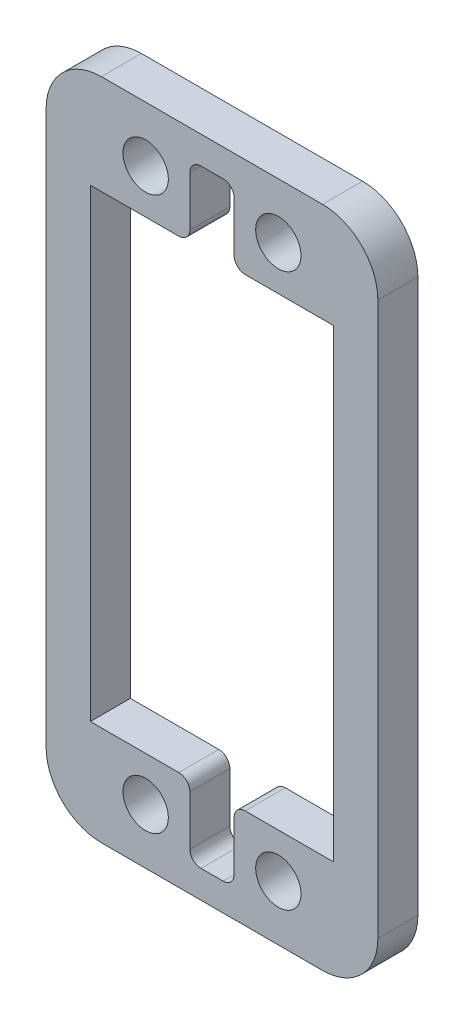
SolidWorks part; units mm, degrees
ref_plane "Alzado" through (0, 0, 0) normal (0, 0, 1) x (1, 0, 0)
ref_plane "Planta" through (0, 0, 0) normal (0, 1, 0) x (1, 0, 0)
ref_plane "Vista lateral" through (0, 0, 0) normal (1, 0, 0) x (0, 0, -1)
sketch "Croquis1" plane through (0, 0, 0) normal (0, 0, 1) x (1, 0, 0)
  line L0 (-15, 30) -> (15, 30)
  line L1 (15, 30) -> (15, -30)
  line L2 (15, -30) -> (-15, -30)
  line L3 (-15, -30) -> (-15, 30)
  line L4 (0, 0) -> (3.1755, 0) construction
  line L5 (0, 0) -> (0, 1.2752) construction
  dimension "D1" = 60
  dimension "D2" = 30
extrude "Saliente-Extruir1" add sketch "Croquis1" along normal blind 3.62
sketch "Croquis2" plane through (0, 0, 0) normal (0, 0, -1) x (-1, 0, 0)
  line L0 (-11, 21) -> (11, 21)
  line L1 (11, 21) -> (11, -21)
  line L2 (11, -21) -> (-11, -21)
  line L3 (-11, -21) -> (-11, 21)
  line L4 (0, 0) -> (17.9824, 0) construction
  line L5 (0, 0) -> (0, 11.2002) construction
  dimension "D1" = 22
  dimension "D2" = 42
extrude "Cortar-Extruir1" cut sketch "Croquis2" against normal through all
sketch "Croquis3" plane through (0, 0, 0) normal (0, 0, -1) x (-1, 0, 0)
  line L0 (0, 0) -> (-26.2125, 0) construction
  line L1 (0, 0) -> (0, 9.0898) construction
  line L2 (-2, 21) -> (-2, 27.5)
  line L3 (11, 21) -> (-11, 21) construction
  line L4 (-2, 27.5) -> (2, 27.5)
  line L5 (2, 27.5) -> (2, -27.5)
  line L6 (2, -27.5) -> (-2, -27.5)
  line L7 (-2, -27.5) -> (-2, 21)
  circle A0 centre (-6, 25) radius 2.05
  circle A1 centre (6, 25) radius 2.05
  circle A2 centre (-6, -25) radius 2.05
  circle A3 centre (6, -25) radius 2.05
  dimension "D1" = 4.1
  dimension "D2" = 4.1
  dimension "D3" = 4.1
  dimension "D4" = 4.1
  dimension "D5" = 12
  dimension "D6" = 12
  dimension "D7" = 50
  dimension "D8" = 25
  dimension "D9" = 4
  dimension "D10" = 55
extrude "Cortar-Extruir2" cut sketch "Croquis3" against normal through all
fillet "Redondeo1" radius 5 4 edges at (-15, -30, 1.81) (15, -30, 1.81) (15, 30, 1.81) (-15, 30, 1.81)
fillet "Redondeo3" radius 1 8 edges at (-2, -27.5, 1.81) (-2, -21, 1.81) (2, -21, 1.81) (2, -27.5, 1.81) (2, 27.5, 1.81) (-2, 27.5, 1.81) (2, 21, 1.81) (-2, 21, 1.81)
